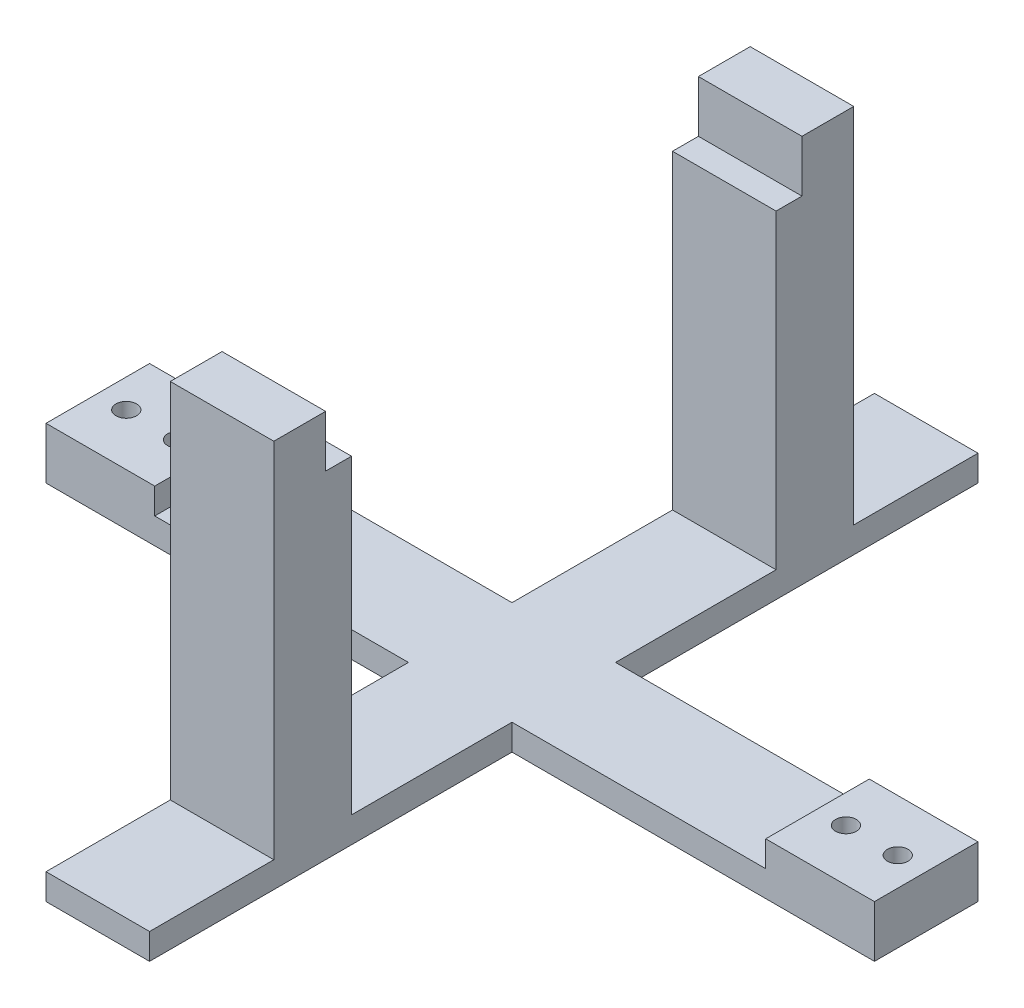
SolidWorks part; units mm, degrees
material "ABS"
ref_plane "Front Plane" through (0, 0, 0) normal (0, 0, 1) x (1, 0, 0)
ref_plane "Top Plane" through (0, 0, 0) normal (0, 1, 0) x (1, 0, 0)
ref_plane "Right Plane" through (0, 0, 0) normal (1, 0, 0) x (0, 0, -1)
sketch "Sketch2" plane through (0, 0, 0) normal (0, 1, 0) x (1, 0, 0)
  line L0 (-10, 1.25) -> (-10, 10) construction
  line L1 (-80, -10) -> (-10, -10)
  line L2 (-80, -10) -> (-80, 10)
  line L3 (-80, 10) -> (-10, 10)
  line L4 (80, -10) -> (80, 10)
  line L5 (-80, -10) -> (-10, -1.25) construction
  line L6 (-80, 10) -> (0, 0) construction
  line L7 (10, -80) -> (-10, -80)
  line L8 (10, -80) -> (10, -10)
  line L9 (10, 80) -> (-10, 80)
  line L10 (-10, -80) -> (-10, -10)
  line L11 (1.25, -10) -> (0, 0) construction
  line L12 (10, 80) -> (1.25, 10) construction
  line L13 (-10, 10) -> (-10, 80)
  line L14 (0, 0) -> (-1.25, 10) construction
  line L15 (-1.25, 10) -> (-10, 80) construction
  line L16 (1.25, 10) -> (0, 0) construction
  line L17 (0, 0) -> (-1.25, -10) construction
  line L18 (10, 1.25) -> (10, 10) construction
  line L19 (10, 10) -> (10, 80)
  line L20 (1.25, 10) -> (10, 10) construction
  line L21 (10, 10) -> (80, 10)
  line L22 (0, 0) -> (10, 1.25) construction
  line L23 (10, 1.25) -> (80, 10) construction
  line L24 (0, 0) -> (10, -1.25) construction
  line L25 (10, -1.25) -> (80, -10) construction
  line L26 (1.25, -10) -> (10, -10) construction
  line L27 (10, -10) -> (80, -10)
  line L28 (10, -80) -> (1.25, -10) construction
  line L29 (-1.25, -10) -> (-10, -80) construction
  line L30 (-10, -10) -> (-1.25, -10) construction
  line L31 (-1.25, -10) -> (1.25, -10) construction
  line L32 (-10, -10) -> (-10, -1.25) construction
  line L33 (-10, -1.25) -> (-10, 1.25) construction
  line L34 (-10, -1.25) -> (0, 0) construction
  line L35 (10, -1.25) -> (10, 1.25) construction
  line L36 (10, -10) -> (10, -1.25) construction
  line L37 (-1.25, 10) -> (1.25, 10) construction
  line L38 (-10, 10) -> (-1.25, 10) construction
  point P0 (0, 0)
  point P5 (0, 0)
  dimension "D1" = 20
  dimension "D2" = 160
  dimension "D3" = 160
  dimension "D4" = 20
extrude "Boss-Extrude1" add sketch "Sketch2" along normal blind 5
sketch "Sketch3" plane through (0, 5, 0) normal (0, 1, 0) x (1, 0, 0)
  line L0 (-80, -10) -> (-10, -10) construction
  line L1 (-80, 10) -> (-59, 10)
  line L2 (-80, 10) -> (-80, -10)
  line L3 (-80, -10) -> (-59, -10)
  line L4 (-59, 10) -> (-59, -10)
  line L5 (-10, 10) -> (10, -10) construction
  line L10 (-10, -10) -> (10, 10) construction
  dimension "D1" = 21
extrude "Boss-Extrude2" add sketch "Sketch3" along normal blind 5
sketch "Sketch4" plane through (0, 10, 0) normal (0, 1, 0) x (1, 0, 0)
  line L0 (-80, 0) -> (-59, 0) construction
  line L1 (-80, 10) -> (-80, -10) construction
  line L2 (-59, -10) -> (-59, 10) construction
  point P6 (-74.5, 0)
  point P7 (-64.5, 0)
  dimension "D1" = 5.5
  dimension "D2" = 5.5
hole_wizard "Ø4.0mm Dowel Hole1" positions "Sketch4" profile "Sketch5" hole size "Ø4.0" standard "ANSI Metric"
sketch "Sketch5" plane through (-64.5, 10, 0) normal (1, 0, 0) x (0, 0, 1)
  line L0 (0, 0) -> (0, 118.8308)
  line L1 (0, 118.8308) -> (2, 117.6291)
  line L2 (2, 117.6291) -> (2, 0)
  line L5 (2, 0) -> (0, 0)
  line L10 (0, 118.8308) -> (-2, 117.6291) construction
  line L11 (0, -6.35) -> (0, 107.95) construction
  dimension "Hole Dia." = 4
  dimension "Hole Depth" = 117.6291
  dimension "Drill Angle" = 118
mirror "Mirror1" about plane through (0, 0, 0) normal (1, 0, 0) of "Ø4.0mm Dowel Hole1", "Boss-Extrude2"
ref_plane "Plane1" through (-59, 10, 10) normal (0, -1, 0) x (-1, 0, 0)
sketch "Sketch15" plane through (0, 5, 0) normal (0, 1, 0) x (1, 0, 0)
  line L0 (0, 0) -> (0, 41) construction
  line L1 (0, 41) -> (10, 41) construction
  line L2 (10, 10) -> (10, 80) construction
  line L4 (10, 41) -> (-10, 41)
  line L5 (10, 41) -> (10, 56)
  line L6 (10, 56) -> (-10, 56)
  line L7 (-10, 41) -> (-10, 56)
  line L8 (-10, 80) -> (-10, 10) construction
  line L9 (0, 0) -> (20.547, 0) construction
  line L10 (10, -56) -> (-10, -56)
  line L11 (-10, -41) -> (-10, -56)
  line L12 (10, -41) -> (-10, -41)
  line L13 (10, -41) -> (10, -56)
  dimension "D1" = 41
  dimension "D2" = 15
  dimension "D3" = 20
extrude "Boss-Extrude6" add sketch "Sketch15" along normal blind 60
sketch "Sketch16" plane through (0, 65, 0) normal (0, 1, 0) x (1, 0, 0)
  line L0 (10, 41) -> (10, 46) construction
  line L1 (10, 41) -> (10, 56) construction
  line L2 (0, 0) -> (20.9979, 0) construction
  line L3 (10, 46) -> (-10, 46)
  line L4 (10, 46) -> (10, 56)
  line L5 (10, 56) -> (-10, 56)
  line L6 (-10, 46) -> (-10, 56)
  line L7 (10, -56) -> (-10, -56)
  line L8 (-10, -46) -> (-10, -56)
  line L9 (10, -46) -> (-10, -46)
  line L10 (10, -46) -> (10, -56)
  dimension "D1" = 5
extrude "Boss-Extrude7" add sketch "Sketch16" along normal blind 10
